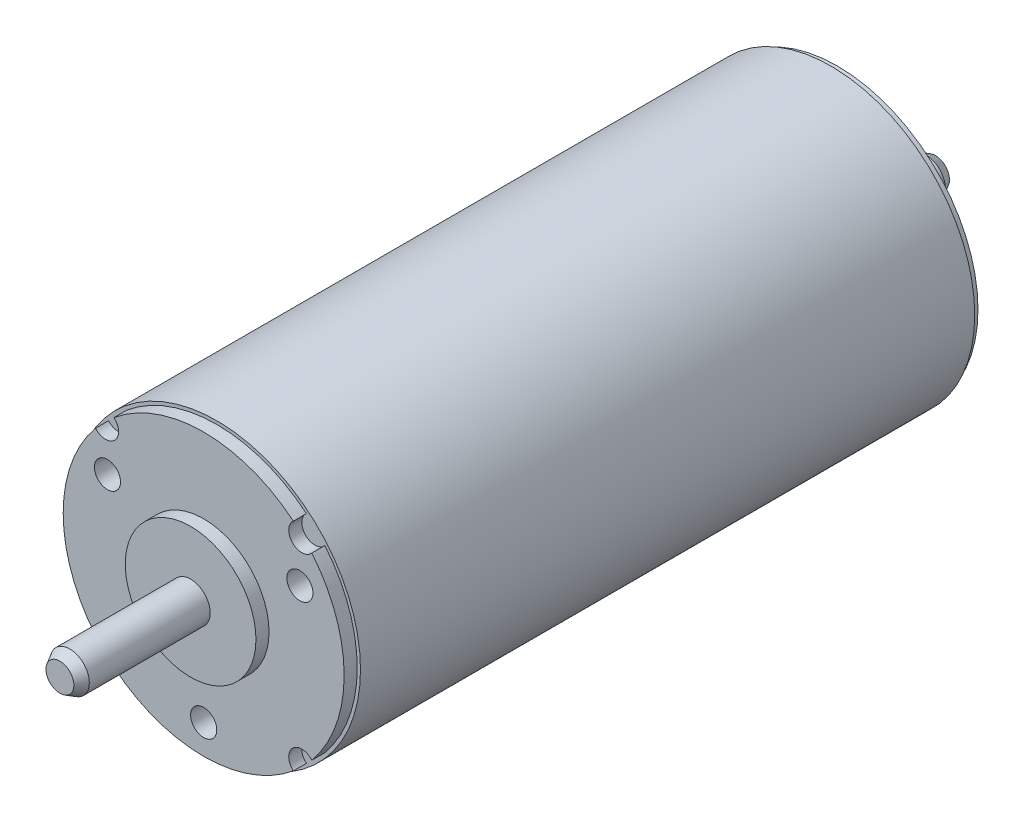
SolidWorks part; units mm, degrees
ref_plane "Front" through (0, 0, 0) normal (0, 0, 1) x (1, 0, 0)
ref_plane "Top" through (0, 0, 0) normal (0, 1, 0) x (1, 0, 0)
ref_plane "Right" through (0, 0, 0) normal (1, 0, 0) x (0, 0, -1)
sketch "Sketch1" plane through (0, 0, 0) normal (0, 0, 1) x (1, 0, 0)
  circle A0 centre (0, 0) radius 11
  dimension "D1" = 22
extrude "Extrude1" add sketch "Sketch1" along normal blind 47
sketch "Sketch2" plane through (0, 0, 47) normal (0, 0, 1) x (1, 0, 0)
  circle A0 centre (0, 0) radius 10.75
  dimension "D1" = 21.5
extrude "Extrude2" add sketch "Sketch2" along normal blind 1
sketch "Sketch3" plane through (0, 0, 0) normal (0, 0, -1) x (-1, 0, 0)
  circle A0 centre (0, 0) radius 10.75
  dimension "D1" = 21.5
extrude "Extrude3" add sketch "Sketch3" along normal blind 0.5
sketch "Sketch4" plane through (0, 0, 48) normal (0, 0, 1) x (1, 0, 0)
  circle A0 centre (0, 0) radius 5
  dimension "D1" = 10
extrude "Extrude4" add sketch "Sketch4" along normal blind 1
sketch "Sketch5" plane through (0, 0, -0.5) normal (0, 0, -1) x (-1, 0, 0)
  circle A0 centre (0, 0) radius 5
  dimension "D1" = 10
extrude "Extrude5" add sketch "Sketch5" along normal blind 1
sketch "Sketch6" plane through (0, 0, 49) normal (0, 0, 1) x (1, 0, 0)
  circle A0 centre (0, 0) radius 1.5
  dimension "D1" = 3
extrude "Extrude6" add sketch "Sketch6" along normal blind 10
sketch "Sketch7" plane through (0, 0, -1.5) normal (0, 0, -1) x (-1, 0, 0)
  circle A0 centre (0, 0) radius 1.5
  dimension "D1" = 3
extrude "Extrude7" add sketch "Sketch7" along normal blind 6.5
chamfer "Chamfer1" distance 0.75 angle 30 2 edges at (1.5, 0, 59) (-1.5, 0, -8)
sketch "Sketch8" plane through (0, 0, 48) normal (0, 0, 1) x (1, 0, 0)
  circle A0 centre (0, -8.5) radius 1
  circle A1 centre (0, 0) radius 1.067 construction
  dimension "D1" = 2
  dimension "D2" = 8.5
extrude "Extrude8" cut sketch "Sketch8" against normal blind 3
pattern_circular "CirPattern1" count 3 over 360 about axis through (0, 0, 0) along (0, 0, 1) of "Extrude8"
sketch "Sketch9" plane through (0, 0, -0.5) normal (0, 0, -1) x (-1, 0, 0)
  circle A0 centre (0, -7.5) radius 0.8
  dimension "D1" = 1.6
  dimension "D2" = 7.5
extrude "Extrude9" cut sketch "Sketch9" against normal blind 2.4
pattern_circular "CirPattern2" count 3 over 360 about axis through (0, 0, 0) along (0, 0, 1) of "Extrude9"
sketch "Sketch10" plane through (0, 0, 48) normal (0, 0, 1) x (1, 0, 0)
  line L0 (0, 0) -> (7.7782, 7.7782) construction
  circle A0 centre (0, 0) radius 11 construction
sketch "Sketch11" plane through (0, 0, 48) normal (0, 0, 1) x (1, 0, 0)
  line L0 (0, 0) -> (7.7782, 7.7782) construction
  arc A0 (8.3303, 6.939) -> (6.9637, 8.3468) centre (7.5079, 7.5079) cw
  arc A1 (6.9637, 8.3468) -> (8.3468, 6.9637) centre (0, 0) cw
  dimension "D1" = 1
  dimension "D2" = 7.5079
extrude "Extrude10" cut sketch "Sketch11" against normal up to surface (1 mm away) contours A1 A0
pattern_circular "CirPattern3" count 4 over 360 about axis through (0, 0, 0) along (0, 0, 1) of "Extrude10"
